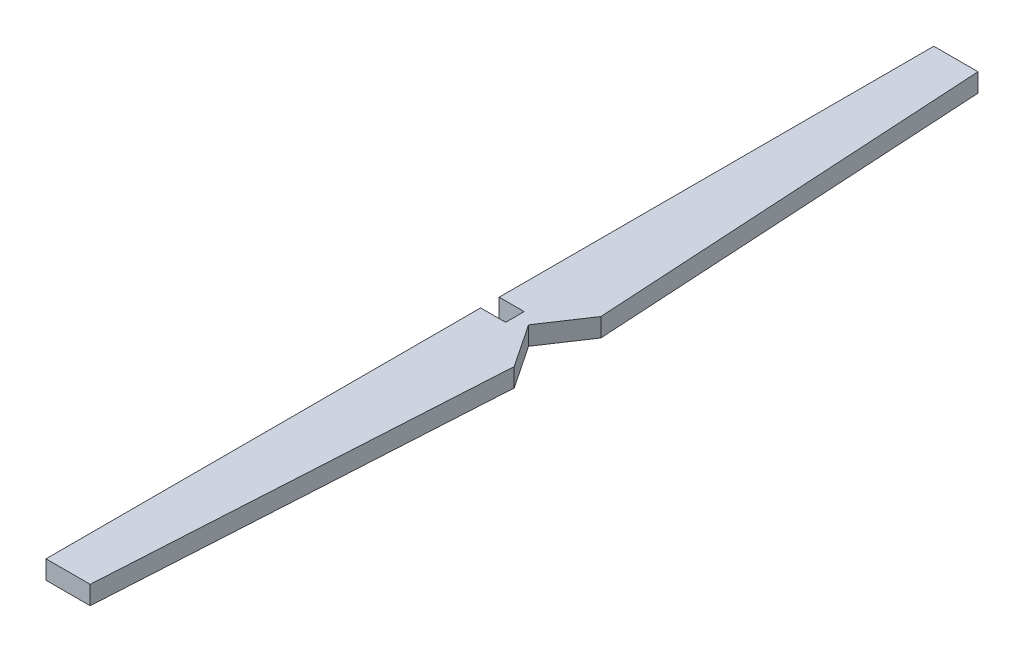
SolidWorks part; units mm, degrees
ref_plane "Front Plane" through (0, 0, 0) normal (0, 0, 1) x (1, 0, 0)
ref_plane "Top Plane" through (0, 0, 0) normal (0, 1, 0) x (1, 0, 0)
ref_plane "Right Plane" through (0, 0, 0) normal (1, 0, 0) x (0, 0, -1)
sketch "Sketch1" plane through (0, 0, 0) normal (0, 1, 0) x (1, 0, 0)
  line L0 (0, 497.2644) -> (0, 7.5) construction
  line L1 (0, 358.35) -> (0, 7.5)
  line L4 (54.5725, 34.9979) -> (35.6506, 358.35)
  line L5 (35.6506, 358.35) -> (0, 358.35)
  line L6 (47.8, 150.7317) -> (0, 150.7317) construction
  line L7 (56.6205, 0) -> (723.1311, 0) construction
  line L8 (54.5725, 34.9979) -> (31.1966, 0)
  line L11 (0, -358.35) -> (0, -497.2644) construction
  line L12 (0, 7.5) -> (20.1804, 7.5)
  line L13 (20.1804, 7.5) -> (20.1804, -7.5)
  line L14 (35.6506, -358.35) -> (0, -358.35)
  line L15 (54.5725, -34.9979) -> (35.6506, -358.35)
  line L16 (54.5725, -34.9979) -> (31.1966, 0)
  line L17 (0, -7.5) -> (20.1804, -7.5)
  line L18 (0, -358.35) -> (0, -7.5)
  point P4 (0, 0)
  point P7 (0, 182.925)
  dimension "D1" = 716.7
  dimension "D2" = 47.8
extrude "Boss-Extrude1" add sketch "Sketch1" along normal blind 15
scale "Scale1" scale about centroid uniform scaling yes scale factor 0.6
